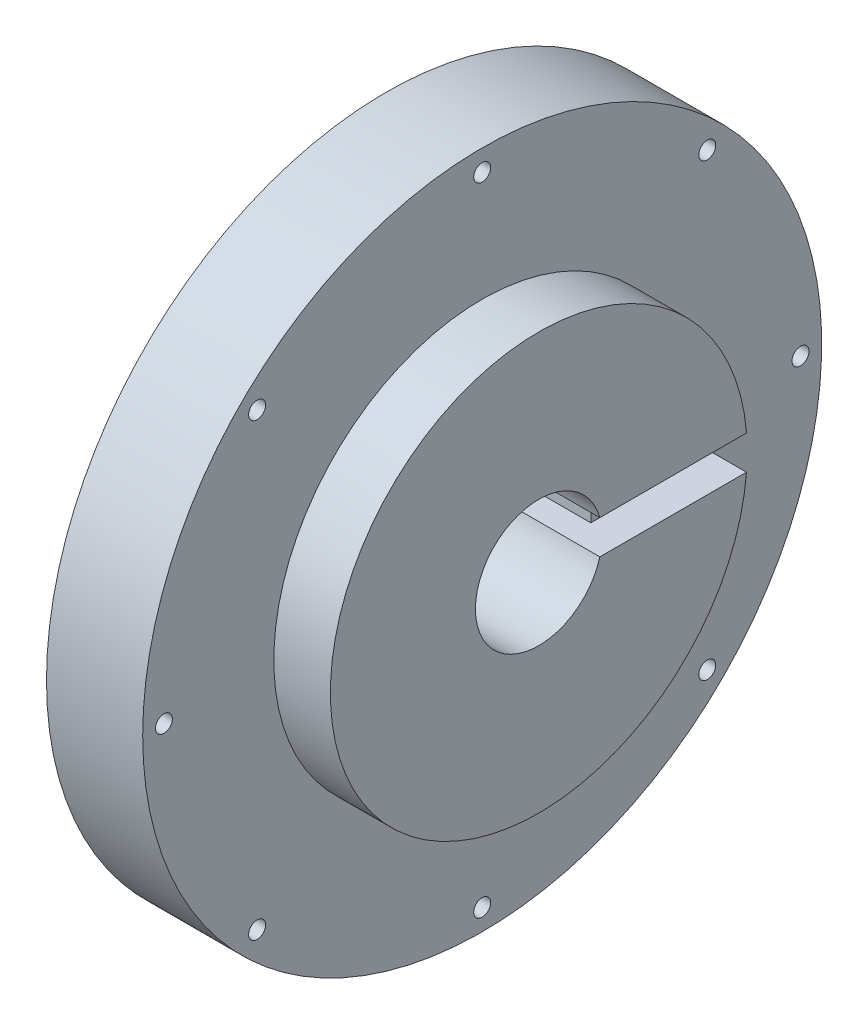
SolidWorks part; units mm, degrees
ref_plane "Front Plane" through (0, 0, 0) normal (0, 0, 1) x (1, 0, 0)
ref_plane "Top Plane" through (0, 0, 0) normal (0, 1, 0) x (1, 0, 0)
ref_plane "Right Plane" through (0, 0, 0) normal (1, 0, 0) x (0, 0, -1)
sketch "Sketch1" plane through (0, 0, 0) normal (0, 0, 1) x (1, 0, 0)
  line L0 (0, 0) -> (0, 60) construction
  line L1 (0, 0) -> (-17, 0)
  line L2 (-17, 0) -> (-17, 25)
  line L3 (-17, 25) -> (-27.05, 25)
  line L4 (-27.05, 25) -> (-27.05, 60)
  line L5 (-27.05, 60) -> (0, 60)
  line L6 (0, 60) -> (0, 0)
  dimension "D1" = 60
  dimension "D2" = 35
  dimension "D3" = 17
  dimension "D4" = 10.05
revolve "Revolve1" add sketch "Sketch1" angle 360 about L5
sketch "upper cirlce" plane through (0, 0, 0) normal (1, 0, 0) x (0, 0, -1)
  circle A0 centre (0, 60) radius 36.83
  dimension "D1" = 73.66
extrude "upper cirlce " add sketch "upper cirlce" along normal blind 10
sketch "ref hex" plane through (0, 0, 0) normal (1, 0, 0) x (0, 0, -1)
  line L1 (0, 109.5) -> (-42.8683, 84.75)
  line L2 (-42.8683, 84.75) -> (-42.8683, 35.25)
  line L3 (-42.8683, 35.25) -> (0, 10.5)
  line L4 (0, 10.5) -> (42.8683, 35.25)
  line L5 (42.8683, 35.25) -> (42.8683, 84.75)
  line L6 (42.8683, 84.75) -> (0, 109.5)
  circle A0 centre (0, 60) radius 42.8683 construction
  dimension "D1" = 49.5
sketch "m3 holes" plane through (0, 0, 0) normal (1, 0, 0) x (0, 0, -1)
  circle A0 centre (-42.8683, 84.75) radius 1.4
  circle A1 centre (-42.8683, 35.25) radius 1.4
  circle A2 centre (0, 10.5) radius 1.4
  circle A3 centre (42.8683, 35.25) radius 1.4
  circle A4 centre (42.8683, 84.75) radius 1.4
  circle A5 centre (0, 109.5) radius 1.4
  dimension "D1" = 2.8
  dimension "D2" = 2.8
  dimension "D3" = 2.8
  dimension "D4" = 2.8
  dimension "D5" = 2.8
  dimension "D6" = 2.8
extrude "holes" [suppressed] cut sketch "m3 holes" against normal blind 16
sketch "pin ref" plane through (-27.05, 0, 0) normal (-1, 0, 0) x (0, 0, 1)
  line L1 (0, 60) -> (18.56, 60)
  line L2 (0, 60) -> (0, 78.56)
  line L3 (0, 78.56) -> (18.56, 78.56)
  line L4 (18.56, 60) -> (18.56, 78.56)
  line L5 (0, 60) -> (18.56, 60)
  line L6 (0, 60) -> (0, 41.44)
  line L7 (0, 41.44) -> (18.56, 41.44)
  line L8 (18.56, 60) -> (18.56, 41.44)
  line L9 (0, 60) -> (-18.56, 60)
  line L10 (0, 60) -> (0, 41.44)
  line L11 (0, 41.44) -> (-18.56, 41.44)
  line L12 (-18.56, 60) -> (-18.56, 41.44)
  line L13 (0, 60) -> (-18.56, 60)
  line L14 (0, 60) -> (0, 78.56)
  line L15 (0, 78.56) -> (-18.56, 78.56)
  line L16 (-18.56, 60) -> (-18.56, 78.56)
  dimension "D1" = 18.56
  dimension "D2" = 18.56
  dimension "D3" = 18.56
sketch "pin sketch" plane through (-27.05, 0, 0) normal (-1, 0, 0) x (0, 0, 1)
  circle A0 centre (-18.56, 78.56) radius 2
  circle A1 centre (18.56, 78.56) radius 2
  circle A2 centre (18.56, 41.44) radius 2
  circle A3 centre (-18.56, 41.44) radius 2
  dimension "D1" = 4
  dimension "4" = 4
  dimension "D2" = 4
  dimension "D3" = 4
sketch "Sketch2" plane through (0, 0, 0) normal (1, 0, 0) x (0, 0, -1)
  circle A3 centre (0, 116.25) radius 1.5
  dimension "D2" = 3
extrude "Cut-Extrude1" cut sketch "Sketch2" against normal through all both and the other way through all
pattern_circular "CirPattern1" count 8 over 360 about axis through (0, 60, 0) along (1, 0, 0) of "Cut-Extrude1"
extrude "Cut-Extrude2" cut sketch "pin sketch" against normal blind 10
sketch "Sketch3" plane through (10, 0, 0) normal (1, 0, 0) x (0, 0, -1)
  circle A0 centre (0, 60) radius 11.2
extrude "Cut-Extrude3" cut sketch "Sketch3" against normal blind 29
sketch "Sketch4" plane through (-19, 0, 0) normal (1, 0, 0) x (0, 0, -1)
  line L0 (0, 60) -> (18.56, 60) construction
  line L1 (7.2, 63) -> (15.2, 63)
  line L2 (7.2, 63) -> (7.2, 57)
  line L3 (7.2, 57) -> (15.2, 57)
  line L4 (15.2, 63) -> (15.2, 57)
  line L5 (7.2, 63) -> (15.2, 57) construction
  line L6 (7.2, 57) -> (15.2, 63) construction
  circle A0 centre (0, 60) radius 11.2 construction
  point P0 (11.2, 60)
  dimension "D1" = 6
  dimension "D2" = 8
extrude "Cut-Extrude4" cut sketch "Sketch4" along normal blind 70
sketch "Sketch6" plane through (10, 0, 0) normal (1, 0, 0) x (0, 0, -1)
  line L5 (15.2, 63) -> (37.5465, 63)
  line L6 (15.2, 63) -> (15.2, 57)
  line L7 (15.2, 57) -> (37.5465, 57)
  line L8 (37.5465, 63) -> (37.5465, 57)
extrude "Cut-Extrude5" cut sketch "Sketch6" against normal blind 6
sketch "Sketch7" plane through (-19, 0, 0) normal (1, 0, 0) x (0, 0, -1)
  line L1 (15.2, 63) -> (-1.9896, 63)
  line L2 (15.2, 63) -> (15.2, 57)
  line L3 (15.2, 57) -> (-1.9896, 57)
  line L4 (-1.9896, 63) -> (-1.9896, 57)
extrude "Cut-Extrude6" cut sketch "Sketch7" against normal blind 4
